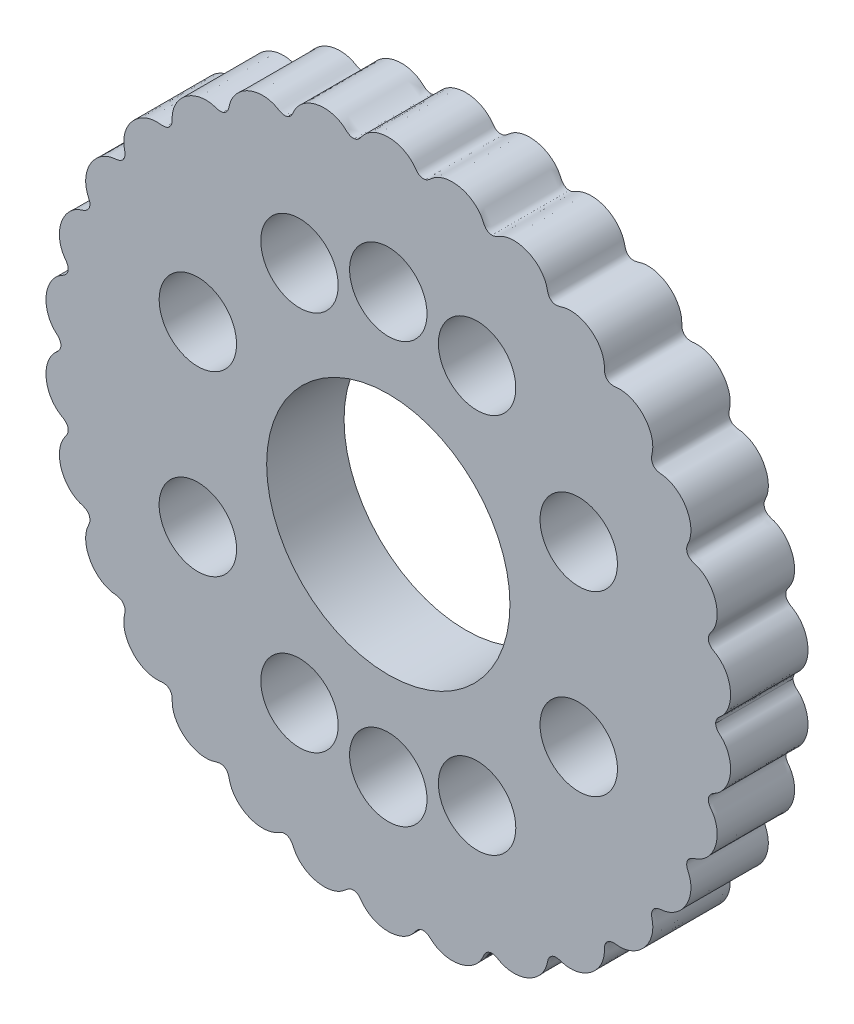
SolidWorks part; units mm, degrees
ref_plane "Plan de face" through (0, 0, 0) normal (0, 0, 1) x (1, 0, 0)
ref_plane "Plan de dessus" through (0, 0, 0) normal (0, 1, 0) x (1, 0, 0)
ref_plane "Plan de droite" through (0, 0, 0) normal (1, 0, 0) x (0, 0, -1)
sketch "Esquisse1" plane through (0, 0, 0) normal (0, 0, 1) x (1, 0, 0)
  line L0 (-1000, 0) -> (49000, 0) construction
  spline S0 degree 4 poles (29.8631, 8.2305) (29.8499, 8.1217) (29.8133, 7.9053) (29.7416, 7.64) (29.6157, 7.3353) (29.4839, 7.095) (29.3642, 6.911) (29.2467, 6.7537) (29.1538, 6.6056) (29.0902, 6.432) (29.0737, 6.2397) (29.1354, 6.023) (29.2904, 5.838) (29.4774, 5.7198) (29.6579, 5.6163) (29.8231, 5.5082) (30.0196, 5.3594) (30.2372, 5.1583) (30.5232, 4.8242) (30.8216, 4.3213) (31.0469, 3.679) (31.1337, 2.9091) (31.0567, 2.2277) (30.8902, 1.7108) (30.7109, 1.353) (30.5728, 1.1334) (30.4496, 0.9663) (30.3139, 0.8094) (30.1671, 0.6626) (30.0393, 0.549) (29.9425, 0.4546) (29.8803, 0.3777) (29.8449, 0.3262) (29.8141, 0.2716) (29.7888, 0.2141) (29.7717, 0.1632) (29.761, 0.1169) (29.7536, 0.0672) (29.7495, 0.017) (29.7494, -0.0206) (29.7556, -0.0898) (29.7678, -0.1499) (29.7904, -0.2203) (29.8284, -0.303) (29.8828, -0.3847) (29.9529, -0.4642) (30.04, -0.5488) (30.1416, -0.6407) (30.2572, -0.7512) (30.3813, -0.8854) (30.4962, -1.0277) (30.6276, -1.2147) (30.7721, -1.4641) (30.9126, -1.7829) (31.0276, -2.1744) (31.0935, -2.591) (31.107, -3.0187) (31.0662, -3.4508) (30.9693, -3.8803) (30.8145, -4.2991) (30.6117, -4.6792) (30.3965, -4.9766) (30.1917, -5.1998) (30.0146, -5.3603) (29.8643, -5.4786) (29.7061, -5.5858) (29.542, -5.684) (29.3671, -5.785) (29.2042, -5.9269) (29.0936, -6.1295) (29.0703, -6.371) (29.1391, -6.5914) (29.2598, -6.7697) (29.3791, -6.934) (29.4834, -7.0955) (29.5997, -7.3056) (29.715, -7.5703) (29.8147, -7.8969) (29.8798, -8.2857) (29.896, -8.684) (29.8631, -9.0858) (29.7829, -9.4799) (29.6574, -9.8612) (29.4885, -10.2243) (29.2783, -10.5643) (29.0303, -10.8742) (28.7824, -11.1148) (28.5506, -11.2952) (28.3468, -11.4258) (28.1768, -11.5188) (28.0006, -11.599) (27.8193, -11.6676) (27.6244, -11.7296) (27.4217, -11.8089) (27.242, -11.9571) (27.1301, -12.1734) (27.113, -12.404) (27.1707, -12.6114) (27.2542, -12.795) (27.3276, -12.9715) (27.3906, -13.1518) (27.4404, -13.3363) (27.4866, -13.5706) (27.5177, -13.8717) (27.5133, -14.2384) (27.4499, -14.6642) (27.3252, -15.0926) (27.1465, -15.4978) (26.919, -15.8739) (26.6474, -16.2153) (26.3365, -16.5168) (26.0024, -16.764) (25.654, -16.9563) (25.3418, -17.0779) (25.0791, -17.148) (24.8562, -17.1866) (24.6765, -17.2082) (24.4854, -17.2287) (24.2872, -17.2853) (24.1038, -17.4139) (23.9758, -17.6159) (23.9376, -17.8434) (23.9703, -18.0586) (24.0141, -18.2584) (24.0453, -18.4498) (24.0639, -18.6424) (24.0684, -18.8361) (24.0572, -19.0779) (24.0169, -19.3689) (23.9324, -19.7039) (23.7881, -20.0736) (23.5988, -20.4256) (23.3687, -20.7534) (23.1013, -21.0528) (22.8001, -21.3193) (22.4685, -21.5487) (22.1155, -21.7338) (21.7463, -21.8718) (21.4135, -21.9488) (21.1267, -21.9813) (20.8866, -21.9856) (20.6945, -21.9761) (20.4927, -21.9549) (20.2778, -21.9395) (20.0526, -21.9901) (19.8551, -22.131) (19.7349, -22.3281) (19.6935, -22.5401) (19.6935, -22.7421) (19.6905, -22.9333) (19.6768, -23.124) (19.6495, -23.3133) (19.599, -23.5469) (19.5081, -23.8358) (19.3582, -24.1709) (19.1304, -24.5365) (18.8451, -24.88) (18.5216, -25.1787) (18.1677, -25.4301) (17.7906, -25.6322) (17.3968, -25.7835) (17.0003, -25.8796) (16.6085, -25.9224) (16.2742, -25.9148) (16.002, -25.8785) (15.7793, -25.8278) (15.6036, -25.7769) (15.4169, -25.7147) (15.2087, -25.6689) (14.9779, -25.6954) (14.7639, -25.8189) (14.6256, -26.0056) (14.5611, -26.2088) (14.5217, -26.4015) (14.4779, -26.5791) (14.4104, -26.7974) (14.3058, -27.0513) (14.1452, -27.3445) (13.9122, -27.6625) (13.6308, -27.9579) (13.3029, -28.2232) (12.9393, -28.4488) (12.5446, -28.6295) (12.1242, -28.7604) (11.6841, -28.8357) (11.2535, -28.8501) (10.8884, -28.8124) (10.5927, -28.7466) (10.3651, -28.6736) (10.1875, -28.6026) (10.0156, -28.5191) (9.8485, -28.4261) (9.6736, -28.3252) (9.4693, -28.255) (9.2385, -28.2605) (9.0177, -28.3611) (8.8612, -28.5309) (8.7671, -28.7246) (8.6846, -28.91) (8.5968, -29.0812) (8.473, -29.2869) (8.3014, -29.519) (8.0684, -29.7687) (7.7643, -30.0195) (7.4274, -30.2327) (7.0631, -30.4051) (6.6816, -30.5327) (6.2887, -30.6146) (5.8897, -30.6499) (5.4902, -30.6379) (5.0979, -30.5781) (4.7655, -30.4837) (4.4934, -30.3731) (4.2784, -30.2619) (4.1128, -30.1612) (3.9553, -30.0487) (3.8052, -29.926) (3.6541, -29.7882) (3.484, -29.6523) (3.2679, -29.5716) (3.029, -29.5815) (2.8259, -29.676) (2.6778, -29.8193) (2.5645, -29.9746) (2.456, -30.1194) (2.311, -30.2931) (2.119, -30.4856) (1.8576, -30.6952) (1.5168, -30.9007) (1.1357, -31.0665) (0.7192, -31.185) (0.2877, -31.2495) (-0.1517, -31.2585) (-0.592, -31.2106) (-1.0254, -31.1045) (-1.4258, -30.9464) (-1.7456, -30.7669) (-1.9908, -30.5894) (-2.1706, -30.4322) (-2.3055, -30.2968) (-2.4301, -30.1521) (-2.5463, -30.0003) (-2.6635, -29.8363) (-2.8143, -29.6826) (-3.0226, -29.582) (-3.2659, -29.5708) (-3.484, -29.6523) (-3.654, -29.7882) (-3.8052, -29.926) (-3.9553, -30.0487) (-4.1128, -30.1612) (-4.2784, -30.2619) (-4.4934, -30.3731) (-4.7655, -30.4837) (-5.0979, -30.5781) (-5.4902, -30.6379) (-5.8897, -30.6499) (-6.2887, -30.6146) (-6.6816, -30.5327) (-7.0631, -30.4051) (-7.4274, -30.2327) (-7.7643, -30.0195) (-8.0684, -29.7687) (-8.3014, -29.519) (-8.473, -29.2869) (-8.5968, -29.0812) (-8.6846, -28.91) (-8.7671, -28.7246) (-8.8612, -28.5309) (-9.0177, -28.3611) (-9.2385, -28.2605) (-9.4693, -28.255) (-9.6736, -28.3252) (-9.8485, -28.4261) (-10.0156, -28.5191) (-10.1875, -28.6026) (-10.3651, -28.6736) (-10.5927, -28.7466) (-10.8884, -28.8124) (-11.2535, -28.8501) (-11.6841, -28.8357) (-12.1242, -28.7604) (-12.5446, -28.6295) (-12.9393, -28.4488) (-13.3029, -28.2232) (-13.6308, -27.9579) (-13.9122, -27.6625) (-14.1452, -27.3445) (-14.3058, -27.0513) (-14.4104, -26.7974) (-14.4779, -26.5791) (-14.5217, -26.4015) (-14.5611, -26.2088) (-14.6256, -26.0056) (-14.7639, -25.8189) (-14.9779, -25.6954) (-15.2087, -25.6689) (-15.4169, -25.7147) (-15.6036, -25.7769) (-15.7793, -25.8278) (-16.002, -25.8785) (-16.2742, -25.9148) (-16.6085, -25.9224) (-17.0003, -25.8796) (-17.3968, -25.7835) (-17.7906, -25.6322) (-18.1677, -25.4301) (-18.5216, -25.1787) (-18.8451, -24.88) (-19.1304, -24.5365) (-19.3582, -24.1709) (-19.5081, -23.8358) (-19.599, -23.5469) (-19.6495, -23.3133) (-19.6768, -23.124) (-19.6905, -22.9333) (-19.6935, -22.7421) (-19.6935, -22.5401) (-19.7349, -22.3281) (-19.8551, -22.131) (-20.0526, -21.9901) (-20.2778, -21.9395) (-20.4927, -21.9549) (-20.6945, -21.9761) (-20.8866, -21.9856) (-21.1267, -21.9813) (-21.4135, -21.9488) (-21.7463, -21.8718) (-22.1155, -21.7338) (-22.4685, -21.5487) (-22.8001, -21.3193) (-23.1013, -21.0528) (-23.3687, -20.7534) (-23.5988, -20.4256) (-23.7881, -20.0736) (-23.9324, -19.7039) (-24.0169, -19.3689) (-24.0572, -19.0779) (-24.0684, -18.8361) (-24.0639, -18.6424) (-24.0453, -18.4498) (-24.0141, -18.2584) (-23.9703, -18.0586) (-23.9376, -17.8434) (-23.9758, -17.6159) (-24.1038, -17.4139) (-24.2872, -17.2853) (-24.4854, -17.2287) (-24.6765, -17.2082) (-24.8562, -17.1866) (-25.0791, -17.148) (-25.3418, -17.0779) (-25.654, -16.9563) (-26.0024, -16.764) (-26.3365, -16.5168) (-26.6474, -16.2153) (-26.919, -15.8739) (-27.1465, -15.4978) (-27.3252, -15.0926) (-27.4499, -14.6642) (-27.5133, -14.2384) (-27.5177, -13.8717) (-27.4866, -13.5706) (-27.4404, -13.3363) (-27.3906, -13.1518) (-27.3276, -12.9715) (-27.2542, -12.795) (-27.1707, -12.6114) (-27.113, -12.404) (-27.1301, -12.1734) (-27.242, -11.9571) (-27.4217, -11.8089) (-27.6244, -11.7296) (-27.8193, -11.6676) (-28.0006, -11.599) (-28.1768, -11.5188) (-28.3468, -11.4258) (-28.5506, -11.2952) (-28.7824, -11.1148) (-29.0303, -10.8742) (-29.2783, -10.5643) (-29.4885, -10.2243) (-29.6574, -9.8612) (-29.7829, -9.4799) (-29.8631, -9.0858) (-29.896, -8.684) (-29.8798, -8.2857) (-29.8147, -7.8969) (-29.715, -7.5703) (-29.5997, -7.3056) (-29.4834, -7.0955) (-29.3791, -6.934) (-29.2598, -6.7697) (-29.1391, -6.5914) (-29.0703, -6.371) (-29.0936, -6.1295) (-29.2042, -5.9269) (-29.3671, -5.785) (-29.542, -5.684) (-29.7061, -5.5858) (-29.8643, -5.4786) (-30.0146, -5.3603) (-30.1917, -5.1998) (-30.3965, -4.9766) (-30.6117, -4.6792) (-30.8145, -4.2991) (-30.9693, -3.8803) (-31.0662, -3.4508) (-31.107, -3.0187) (-31.0935, -2.591) (-31.0276, -2.1744) (-30.9126, -1.7829) (-30.7537, -1.4222) (-30.58, -1.1364) (-30.4124, -0.919) (-30.2572, -0.7512) (-30.1416, -0.6407) (-30.04, -0.5488) (-29.9529, -0.4642) (-29.8828, -0.3847) (-29.8284, -0.303) (-29.7904, -0.2203) (-29.7678, -0.1499) (-29.7556, -0.0898) (-29.7494, -0.0206) (-29.7495, 0.0226) (-29.7561, 0.094) (-29.7693, 0.1557) (-29.7888, 0.2141) (-29.8141, 0.2716) (-29.8449, 0.3262) (-29.8803, 0.3778) (-29.9262, 0.4344) (-29.9834, 0.4947) (-30.0703, 0.5765) (-30.1854, 0.6811) (-30.3139, 0.8093) (-30.4835, 1.0056) (-30.6621, 1.2611) (-30.8291, 1.576) (-30.9678, 1.9517) (-31.0574, 2.3341) (-31.1011, 2.7166) (-31.1012, 3.1978) (-31.0148, 3.7704) (-30.8216, 4.3213) (-30.5232, 4.8242) (-30.2372, 5.1583) (-30.0196, 5.3594) (-29.8231, 5.5082) (-29.6579, 5.6163) (-29.4774, 5.7198) (-29.2904, 5.838) (-29.1354, 6.023) (-29.0737, 6.2397) (-29.0902, 6.432) (-29.1538, 6.6056) (-29.2467, 6.7537) (-29.3642, 6.911) (-29.4839, 7.095) (-29.6157, 7.3353) (-29.7416, 7.64) (-29.8133, 7.9053) (-29.8499, 8.1217) (-29.8631, 8.2305) knots 0 0 0 0 0 0.003392 0.006784 0.00848 0.010176 0.011872 0.013568 0.014566 0.015563 0.017559 0.01944 0.02132 0.022846 0.024371 0.025896 0.027421 0.030471 0.033522 0.039468 0.045414 0.051361 0.057307 0.060517 0.062121 0.063726 0.065331 0.066935 0.06854 0.070145 0.070628 0.071112 0.071596 0.07208 0.072564 0.073048 0.073289 0.073531 0.074015 0.07448 0.074945 0.07541 0.075875 0.076805 0.077735 0.078442 0.079149 0.080563 0.081977 0.083391 0.084805 0.086218 0.089046 0.092302 0.095557 0.098813 0.102069 0.105514 0.10896 0.112405 0.115851 0.118808 0.120287 0.121766 0.123244 0.124723 0.126202 0.12768 0.1295 0.131319 0.133154 0.134989 0.136475 0.137961 0.139448 0.140934 0.143906 0.146878 0.14999 0.153103 0.156215 0.159327 0.162414 0.1655 0.168586 0.171672 0.174668 0.176165 0.177663 0.179161 0.180659 0.182156 0.183654 0.185506 0.187357 0.189175 0.190994 0.192471 0.193949 0.195426 0.196904 0.198382 0.199859 0.202814 0.206257 0.2097 0.213143 0.216586 0.219928 0.22327 0.226613 0.229955 0.232755 0.235555 0.236955 0.238355 0.239755 0.241155 0.242909 0.244663 0.246515 0.248366 0.249864 0.251362 0.252859 0.254357 0.255855 0.257353 0.260348 0.263434 0.266521 0.269607 0.272693 0.275805 0.278918 0.28203 0.285143 0.288115 0.291087 0.292573 0.294059 0.295545 0.297031 0.298866 0.300701 0.302521 0.30434 0.305819 0.307297 0.308776 0.310255 0.311733 0.313212 0.31617 0.319615 0.323061 0.326506 0.329952 0.333207 0.336463 0.339719 0.342974 0.345802 0.34863 0.350043 0.351457 0.352871 0.354285 0.356145 0.358005 0.359865 0.361725 0.363139 0.364553 0.365967 0.367381 0.370208 0.373036 0.376292 0.379547 0.382803 0.386059 0.389504 0.39295 0.396395 0.399841 0.402798 0.404277 0.405755 0.407234 0.408713 0.410191 0.41167 0.41349 0.415309 0.417144 0.418979 0.420465 0.421951 0.423437 0.424923 0.427896 0.430868 0.43398 0.437092 0.440205 0.443317 0.446403 0.44949 0.452576 0.455662 0.458657 0.460155 0.461653 0.463151 0.464649 0.466146 0.467644 0.469495 0.471347 0.473101 0.474856 0.476256 0.477656 0.479056 0.480456 0.483256 0.486055 0.489398 0.49274 0.496082 0.499424 0.502867 0.50631 0.509753 0.513196 0.516151 0.517629 0.519106 0.520584 0.522061 0.523539 0.525016 0.526835 0.528653 0.530505 0.532356 0.533854 0.535351 0.536849 0.538347 0.539845 0.541343 0.544338 0.547424 0.55051 0.553597 0.556683 0.559795 0.562908 0.56602 0.569132 0.572104 0.575077 0.576563 0.578049 0.579535 0.581021 0.582856 0.584691 0.58651 0.58833 0.589809 0.591287 0.592766 0.594245 0.595723 0.597202 0.600159 0.603605 0.60705 0.610496 0.613941 0.617197 0.620453 0.623708 0.626964 0.629792 0.632619 0.634033 0.635447 0.636861 0.638275 0.640135 0.641995 0.643855 0.645715 0.647129 0.648543 0.649957 0.65137 0.654198 0.657026 0.660281 0.663537 0.666793 0.670048 0.673494 0.676939 0.680385 0.68383 0.686788 0.688267 0.689745 0.691224 0.692703 0.694181 0.69566 0.697479 0.699299 0.701134 0.702969 0.704455 0.705941 0.707427 0.708913 0.711885 0.714857 0.71797 0.721082 0.724195 0.727307 0.730393 0.733479 0.736566 0.739652 0.742647 0.744145 0.745643 0.747141 0.748638 0.750136 0.751634 0.753485 0.755337 0.757091 0.758845 0.760245 0.761645 0.763045 0.764445 0.767245 0.770045 0.773387 0.77673 0.780072 0.783414 0.786857 0.7903 0.793743 0.797186 0.800141 0.801618 0.803096 0.804574 0.806051 0.807529 0.809006 0.810825 0.812643 0.814494 0.816346 0.817844 0.819341 0.820839 0.822337 0.823835 0.825332 0.828328 0.831414 0.8345 0.837586 0.840673 0.843785 0.846897 0.85001 0.853122 0.856094 0.859066 0.860552 0.862039 0.863525 0.865011 0.866846 0.868681 0.8705 0.87232 0.873798 0.875277 0.876756 0.878234 0.879713 0.881192 0.884149 0.887595 0.89104 0.894486 0.897931 0.901187 0.904443 0.907698 0.910954 0.913782 0.916609 0.918023 0.919437 0.920851 0.921558 0.922265 0.923195 0.924125 0.92459 0.925055 0.92552 0.925985 0.926469 0.926952 0.927436 0.92792 0.928404 0.928888 0.929372 0.929855 0.930658 0.93146 0.933065 0.934669 0.936274 0.939483 0.942693 0.945666 0.948639 0.951612 0.954586 0.960532 0.966478 0.969529 0.972579 0.974104 0.975629 0.977154 0.97868 0.98056 0.982441 0.984437 0.985434 0.986432 0.988128 0.989824 0.99152 0.993216 0.996608 1 1 1 1 1 construction
  spline S1 degree 4 poles (29.75, 0) (29.75, -0.0128) (29.751, -0.0384) (29.7556, -0.0898) (29.7678, -0.1499) (29.7904, -0.2203) (29.8284, -0.303) (29.8828, -0.3847) (29.9529, -0.4642) (30.04, -0.5488) (30.1416, -0.6407) (30.2572, -0.7512) (30.3813, -0.8854) (30.4962, -1.0277) (30.6276, -1.2147) (30.7721, -1.4641) (30.9126, -1.7829) (31.0276, -2.1744) (31.0935, -2.591) (31.107, -3.0187) (31.0662, -3.4508) (30.9693, -3.8803) (30.8145, -4.2991) (30.6117, -4.6792) (30.3965, -4.9766) (30.1917, -5.1998) (30.0146, -5.3603) (29.8643, -5.4786) (29.7061, -5.5858) (29.542, -5.684) (29.3671, -5.785) (29.2042, -5.9269) (29.0936, -6.1295) (29.0703, -6.371) (29.1391, -6.5914) (29.2598, -6.7697) (29.3791, -6.934) (29.4834, -7.0955) (29.5997, -7.3056) (29.715, -7.5703) (29.8147, -7.8969) (29.8798, -8.2857) (29.896, -8.684) (29.8631, -9.0858) (29.7829, -9.4799) (29.6574, -9.8612) (29.4885, -10.2243) (29.2783, -10.5643) (29.0303, -10.8742) (28.7824, -11.1148) (28.5506, -11.2952) (28.3468, -11.4258) (28.1768, -11.5188) (28.0006, -11.599) (27.8193, -11.6676) (27.6244, -11.7296) (27.4217, -11.8089) (27.242, -11.9571) (27.1301, -12.1734) (27.113, -12.404) (27.1707, -12.6114) (27.2542, -12.795) (27.3276, -12.9715) (27.3906, -13.1518) (27.4404, -13.3363) (27.4866, -13.5706) (27.5177, -13.8717) (27.5133, -14.2384) (27.4499, -14.6642) (27.3252, -15.0926) (27.1465, -15.4978) (26.919, -15.8739) (26.6474, -16.2153) (26.3365, -16.5168) (26.0024, -16.764) (25.654, -16.9563) (25.3418, -17.0779) (25.0791, -17.148) (24.8562, -17.1866) (24.6765, -17.2082) (24.4854, -17.2287) (24.2872, -17.2853) (24.1038, -17.4139) (23.9758, -17.6159) (23.9376, -17.8434) (23.9703, -18.0586) (24.0141, -18.2584) (24.0453, -18.4498) (24.0639, -18.6424) (24.0684, -18.8361) (24.0572, -19.0779) (24.0169, -19.3689) (23.9324, -19.7039) (23.7881, -20.0736) (23.5988, -20.4256) (23.3687, -20.7534) (23.1013, -21.0528) (22.8001, -21.3193) (22.4685, -21.5487) (22.1155, -21.7338) (21.7463, -21.8718) (21.4135, -21.9488) (21.1267, -21.9813) (20.8866, -21.9856) (20.6945, -21.9761) (20.4927, -21.9549) (20.2778, -21.9395) (20.0526, -21.9901) (19.8551, -22.131) (19.7349, -22.3281) (19.6935, -22.5401) (19.6935, -22.7421) (19.6905, -22.9333) (19.6768, -23.124) (19.6495, -23.3133) (19.599, -23.5469) (19.5081, -23.8358) (19.3582, -24.1709) (19.1304, -24.5365) (18.8451, -24.88) (18.5216, -25.1787) (18.1677, -25.4301) (17.7906, -25.6322) (17.3968, -25.7835) (17.0003, -25.8796) (16.6085, -25.9224) (16.2742, -25.9148) (16.002, -25.8785) (15.7793, -25.8278) (15.6036, -25.7769) (15.4169, -25.7147) (15.2087, -25.6689) (14.9779, -25.6954) (14.7639, -25.8189) (14.6256, -26.0056) (14.5611, -26.2088) (14.5217, -26.4015) (14.4779, -26.5791) (14.4104, -26.7974) (14.3058, -27.0513) (14.1452, -27.3445) (13.9122, -27.6625) (13.6308, -27.9579) (13.3029, -28.2232) (12.9393, -28.4488) (12.5446, -28.6295) (12.1242, -28.7604) (11.6841, -28.8357) (11.2535, -28.8501) (10.8884, -28.8124) (10.5927, -28.7466) (10.3651, -28.6736) (10.1875, -28.6026) (10.0156, -28.5191) (9.8485, -28.4261) (9.6736, -28.3252) (9.4693, -28.255) (9.2385, -28.2605) (9.0177, -28.3611) (8.8612, -28.5309) (8.7671, -28.7246) (8.6846, -28.91) (8.5968, -29.0812) (8.473, -29.2869) (8.3014, -29.519) (8.0684, -29.7687) (7.7643, -30.0195) (7.4274, -30.2327) (7.0631, -30.4051) (6.6816, -30.5327) (6.2887, -30.6146) (5.8897, -30.6499) (5.4902, -30.6379) (5.0979, -30.5781) (4.7655, -30.4837) (4.4934, -30.3731) (4.2784, -30.2619) (4.1128, -30.1612) (3.9553, -30.0487) (3.8052, -29.926) (3.6541, -29.7882) (3.484, -29.6523) (3.2679, -29.5716) (3.029, -29.5815) (2.8259, -29.676) (2.6778, -29.8193) (2.5645, -29.9746) (2.456, -30.1194) (2.311, -30.2931) (2.119, -30.4856) (1.8576, -30.6952) (1.5168, -30.9007) (1.1357, -31.0665) (0.7192, -31.185) (0.2877, -31.2495) (-0.1517, -31.2585) (-0.592, -31.2106) (-1.0254, -31.1045) (-1.4258, -30.9464) (-1.7456, -30.7669) (-1.9908, -30.5894) (-2.1706, -30.4322) (-2.3055, -30.2968) (-2.4301, -30.1521) (-2.5463, -30.0003) (-2.6635, -29.8363) (-2.8143, -29.6826) (-3.0226, -29.582) (-3.2659, -29.5708) (-3.484, -29.6523) (-3.654, -29.7882) (-3.8052, -29.926) (-3.9553, -30.0487) (-4.1128, -30.1612) (-4.2784, -30.2619) (-4.4934, -30.3731) (-4.7655, -30.4837) (-5.0979, -30.5781) (-5.4902, -30.6379) (-5.8897, -30.6499) (-6.2887, -30.6146) (-6.6816, -30.5327) (-7.0631, -30.4051) (-7.4274, -30.2327) (-7.7643, -30.0195) (-8.0684, -29.7687) (-8.3014, -29.519) (-8.473, -29.2869) (-8.5968, -29.0812) (-8.6846, -28.91) (-8.7671, -28.7246) (-8.8612, -28.5309) (-9.0177, -28.3611) (-9.2385, -28.2605) (-9.4693, -28.255) (-9.6736, -28.3252) (-9.8485, -28.4261) (-10.0156, -28.5191) (-10.1875, -28.6026) (-10.3651, -28.6736) (-10.5927, -28.7466) (-10.8884, -28.8124) (-11.2535, -28.8501) (-11.6841, -28.8357) (-12.1242, -28.7604) (-12.5446, -28.6295) (-12.9393, -28.4488) (-13.3029, -28.2232) (-13.6308, -27.9579) (-13.9122, -27.6625) (-14.1452, -27.3445) (-14.3058, -27.0513) (-14.4104, -26.7974) (-14.4779, -26.5791) (-14.5217, -26.4015) (-14.5611, -26.2088) (-14.6256, -26.0056) (-14.7639, -25.8189) (-14.9779, -25.6954) (-15.2087, -25.6689) (-15.4169, -25.7147) (-15.6036, -25.7769) (-15.7793, -25.8278) (-16.002, -25.8785) (-16.2742, -25.9148) (-16.6085, -25.9224) (-17.0003, -25.8796) (-17.3968, -25.7835) (-17.7906, -25.6322) (-18.1677, -25.4301) (-18.5216, -25.1787) (-18.8451, -24.88) (-19.1304, -24.5365) (-19.3582, -24.1709) (-19.5081, -23.8358) (-19.599, -23.5469) (-19.6495, -23.3133) (-19.6768, -23.124) (-19.6905, -22.9333) (-19.6935, -22.7421) (-19.6935, -22.5401) (-19.7349, -22.3281) (-19.8551, -22.131) (-20.0526, -21.9901) (-20.2778, -21.9395) (-20.4927, -21.9549) (-20.6945, -21.9761) (-20.8866, -21.9856) (-21.1267, -21.9813) (-21.4135, -21.9488) (-21.7463, -21.8718) (-22.1155, -21.7338) (-22.4685, -21.5487) (-22.8001, -21.3193) (-23.1013, -21.0528) (-23.3687, -20.7534) (-23.5988, -20.4256) (-23.7881, -20.0736) (-23.9324, -19.7039) (-24.0169, -19.3689) (-24.0572, -19.0779) (-24.0684, -18.8361) (-24.0639, -18.6424) (-24.0453, -18.4498) (-24.0141, -18.2584) (-23.9703, -18.0586) (-23.9376, -17.8434) (-23.9758, -17.6159) (-24.1038, -17.4139) (-24.2872, -17.2853) (-24.4854, -17.2287) (-24.6765, -17.2082) (-24.8562, -17.1866) (-25.0791, -17.148) (-25.3418, -17.0779) (-25.654, -16.9563) (-26.0024, -16.764) (-26.3365, -16.5168) (-26.6474, -16.2153) (-26.919, -15.8739) (-27.1465, -15.4978) (-27.3252, -15.0926) (-27.4499, -14.6642) (-27.5133, -14.2384) (-27.5177, -13.8717) (-27.4866, -13.5706) (-27.4404, -13.3363) (-27.3906, -13.1518) (-27.3276, -12.9715) (-27.2542, -12.795) (-27.1707, -12.6114) (-27.113, -12.404) (-27.1301, -12.1734) (-27.242, -11.9571) (-27.4217, -11.8089) (-27.6244, -11.7296) (-27.8193, -11.6676) (-28.0006, -11.599) (-28.1768, -11.5188) (-28.3468, -11.4258) (-28.5506, -11.2952) (-28.7824, -11.1148) (-29.0303, -10.8742) (-29.2783, -10.5643) (-29.4885, -10.2243) (-29.6574, -9.8612) (-29.7829, -9.4799) (-29.8631, -9.0858) (-29.896, -8.684) (-29.8798, -8.2857) (-29.8147, -7.8969) (-29.715, -7.5703) (-29.5997, -7.3056) (-29.4834, -7.0955) (-29.3791, -6.934) (-29.2598, -6.7697) (-29.1391, -6.5914) (-29.0703, -6.371) (-29.0936, -6.1295) (-29.2042, -5.9269) (-29.3671, -5.785) (-29.542, -5.684) (-29.7061, -5.5858) (-29.8643, -5.4786) (-30.0146, -5.3603) (-30.1917, -5.1998) (-30.3965, -4.9766) (-30.6117, -4.6792) (-30.8145, -4.2991) (-30.9693, -3.8803) (-31.0662, -3.4508) (-31.107, -3.0187) (-31.0935, -2.591) (-31.0276, -2.1744) (-30.9126, -1.7829) (-30.7537, -1.4222) (-30.58, -1.1364) (-30.4124, -0.919) (-30.2572, -0.7512) (-30.1416, -0.6407) (-30.04, -0.5488) (-29.9529, -0.4642) (-29.8828, -0.3847) (-29.8284, -0.303) (-29.7904, -0.2203) (-29.7678, -0.1499) (-29.7556, -0.0898) (-29.751, -0.0384) (-29.75, -0.0128) (-29.75, 0) knots 0.074015 0.074015 0.074015 0.074015 0.074015 0.07448 0.074945 0.07541 0.075875 0.076805 0.077735 0.078442 0.079149 0.080563 0.081977 0.083391 0.084805 0.086218 0.089046 0.092302 0.095557 0.098813 0.102069 0.105514 0.10896 0.112405 0.115851 0.118808 0.120287 0.121766 0.123244 0.124723 0.126202 0.12768 0.1295 0.131319 0.133154 0.134989 0.136475 0.137961 0.139448 0.140934 0.143906 0.146878 0.14999 0.153103 0.156215 0.159327 0.162414 0.1655 0.168586 0.171672 0.174668 0.176165 0.177663 0.179161 0.180659 0.182156 0.183654 0.185506 0.187357 0.189175 0.190994 0.192471 0.193949 0.195426 0.196904 0.198382 0.199859 0.202814 0.206257 0.2097 0.213143 0.216586 0.219928 0.22327 0.226613 0.229955 0.232755 0.235555 0.236955 0.238355 0.239755 0.241155 0.242909 0.244663 0.246515 0.248366 0.249864 0.251362 0.252859 0.254357 0.255855 0.257353 0.260348 0.263434 0.266521 0.269607 0.272693 0.275805 0.278918 0.28203 0.285143 0.288115 0.291087 0.292573 0.294059 0.295545 0.297031 0.298866 0.300701 0.302521 0.30434 0.305819 0.307297 0.308776 0.310255 0.311733 0.313212 0.31617 0.319615 0.323061 0.326506 0.329952 0.333207 0.336463 0.339719 0.342974 0.345802 0.34863 0.350043 0.351457 0.352871 0.354285 0.356145 0.358005 0.359865 0.361725 0.363139 0.364553 0.365967 0.367381 0.370208 0.373036 0.376292 0.379547 0.382803 0.386059 0.389504 0.39295 0.396395 0.399841 0.402798 0.404277 0.405755 0.407234 0.408713 0.410191 0.41167 0.41349 0.415309 0.417144 0.418979 0.420465 0.421951 0.423437 0.424923 0.427896 0.430868 0.43398 0.437092 0.440205 0.443317 0.446403 0.44949 0.452576 0.455662 0.458657 0.460155 0.461653 0.463151 0.464649 0.466146 0.467644 0.469495 0.471347 0.473101 0.474856 0.476256 0.477656 0.479056 0.480456 0.483256 0.486055 0.489398 0.49274 0.496082 0.499424 0.502867 0.50631 0.509753 0.513196 0.516151 0.517629 0.519106 0.520584 0.522061 0.523539 0.525016 0.526835 0.528653 0.530505 0.532356 0.533854 0.535351 0.536849 0.538347 0.539845 0.541343 0.544338 0.547424 0.55051 0.553597 0.556683 0.559795 0.562908 0.56602 0.569132 0.572104 0.575077 0.576563 0.578049 0.579535 0.581021 0.582856 0.584691 0.58651 0.58833 0.589809 0.591287 0.592766 0.594245 0.595723 0.597202 0.600159 0.603605 0.60705 0.610496 0.613941 0.617197 0.620453 0.623708 0.626964 0.629792 0.632619 0.634033 0.635447 0.636861 0.638275 0.640135 0.641995 0.643855 0.645715 0.647129 0.648543 0.649957 0.65137 0.654198 0.657026 0.660281 0.663537 0.666793 0.670048 0.673494 0.676939 0.680385 0.68383 0.686788 0.688267 0.689745 0.691224 0.692703 0.694181 0.69566 0.697479 0.699299 0.701134 0.702969 0.704455 0.705941 0.707427 0.708913 0.711885 0.714857 0.71797 0.721082 0.724195 0.727307 0.730393 0.733479 0.736566 0.739652 0.742647 0.744145 0.745643 0.747141 0.748638 0.750136 0.751634 0.753485 0.755337 0.757091 0.758845 0.760245 0.761645 0.763045 0.764445 0.767245 0.770045 0.773387 0.77673 0.780072 0.783414 0.786857 0.7903 0.793743 0.797186 0.800141 0.801618 0.803096 0.804574 0.806051 0.807529 0.809006 0.810825 0.812643 0.814494 0.816346 0.817844 0.819341 0.820839 0.822337 0.823835 0.825332 0.828328 0.831414 0.8345 0.837586 0.840673 0.843785 0.846897 0.85001 0.853122 0.856094 0.859066 0.860552 0.862039 0.863525 0.865011 0.866846 0.868681 0.8705 0.87232 0.873798 0.875277 0.876756 0.878234 0.879713 0.881192 0.884149 0.887595 0.89104 0.894486 0.897931 0.901187 0.904443 0.907698 0.910954 0.913782 0.916609 0.918023 0.919437 0.920851 0.921558 0.922265 0.923195 0.924125 0.92459 0.925055 0.92552 0.925985 0.925985 0.925985 0.925985 0.925985 construction
  spline S2 degree 4 poles (29.75, 0) (29.75, 0.0128) (29.751, 0.0384) (29.7556, 0.0898) (29.7678, 0.1499) (29.7904, 0.2203) (29.8284, 0.303) (29.8828, 0.3847) (29.9529, 0.4642) (30.04, 0.5488) (30.1416, 0.6407) (30.2572, 0.7512) (30.3813, 0.8854) (30.4962, 1.0277) (30.6276, 1.2147) (30.7721, 1.4641) (30.9126, 1.7829) (31.0276, 2.1744) (31.0935, 2.591) (31.107, 3.0187) (31.0662, 3.4508) (30.9693, 3.8803) (30.8145, 4.2991) (30.6117, 4.6792) (30.3965, 4.9766) (30.1917, 5.1998) (30.0146, 5.3603) (29.8643, 5.4786) (29.7061, 5.5858) (29.542, 5.684) (29.3671, 5.785) (29.2042, 5.9269) (29.0936, 6.1295) (29.0703, 6.371) (29.1391, 6.5914) (29.2598, 6.7697) (29.3791, 6.934) (29.4834, 7.0955) (29.5997, 7.3056) (29.715, 7.5703) (29.8147, 7.8969) (29.8798, 8.2857) (29.896, 8.684) (29.8631, 9.0858) (29.7829, 9.4799) (29.6574, 9.8612) (29.4885, 10.2243) (29.2783, 10.5643) (29.0303, 10.8742) (28.7824, 11.1148) (28.5506, 11.2952) (28.3468, 11.4258) (28.1768, 11.5188) (28.0006, 11.599) (27.8193, 11.6676) (27.6244, 11.7296) (27.4217, 11.8089) (27.242, 11.9571) (27.1301, 12.1734) (27.113, 12.404) (27.1707, 12.6114) (27.2542, 12.795) (27.3276, 12.9715) (27.3906, 13.1518) (27.4404, 13.3363) (27.4866, 13.5706) (27.5177, 13.8717) (27.5133, 14.2384) (27.4499, 14.6642) (27.3252, 15.0926) (27.1465, 15.4978) (26.919, 15.8739) (26.6474, 16.2153) (26.3365, 16.5168) (26.0024, 16.764) (25.654, 16.9563) (25.3418, 17.0779) (25.0791, 17.148) (24.8562, 17.1866) (24.6765, 17.2082) (24.4854, 17.2287) (24.2872, 17.2853) (24.1038, 17.4139) (23.9758, 17.6159) (23.9376, 17.8434) (23.9703, 18.0586) (24.0141, 18.2584) (24.0453, 18.4498) (24.0639, 18.6424) (24.0684, 18.8361) (24.0572, 19.0779) (24.0169, 19.3689) (23.9324, 19.7039) (23.7881, 20.0736) (23.5988, 20.4256) (23.3687, 20.7534) (23.1013, 21.0528) (22.8001, 21.3193) (22.4685, 21.5487) (22.1155, 21.7338) (21.7463, 21.8718) (21.4135, 21.9488) (21.1267, 21.9813) (20.8866, 21.9856) (20.6945, 21.9761) (20.4927, 21.9549) (20.2778, 21.9395) (20.0526, 21.9901) (19.8551, 22.131) (19.7349, 22.3281) (19.6935, 22.5401) (19.6935, 22.7421) (19.6905, 22.9333) (19.6768, 23.124) (19.6495, 23.3133) (19.599, 23.5469) (19.5081, 23.8358) (19.3582, 24.1709) (19.1304, 24.5365) (18.8451, 24.88) (18.5216, 25.1787) (18.1677, 25.4301) (17.7906, 25.6322) (17.3968, 25.7835) (17.0003, 25.8796) (16.6085, 25.9224) (16.2742, 25.9148) (16.002, 25.8785) (15.7793, 25.8278) (15.6036, 25.7769) (15.4169, 25.7147) (15.2087, 25.6689) (14.9779, 25.6954) (14.7639, 25.8189) (14.6256, 26.0056) (14.5611, 26.2088) (14.5217, 26.4015) (14.4779, 26.5791) (14.4104, 26.7974) (14.3058, 27.0513) (14.1452, 27.3445) (13.9122, 27.6625) (13.6308, 27.9579) (13.3029, 28.2232) (12.9393, 28.4488) (12.5446, 28.6295) (12.1242, 28.7604) (11.6841, 28.8357) (11.2535, 28.8501) (10.8884, 28.8124) (10.5927, 28.7466) (10.3651, 28.6736) (10.1875, 28.6026) (10.0156, 28.5191) (9.8485, 28.4261) (9.6736, 28.3252) (9.4693, 28.255) (9.2385, 28.2605) (9.0177, 28.3611) (8.8612, 28.5309) (8.7671, 28.7246) (8.6846, 28.91) (8.5968, 29.0812) (8.473, 29.2869) (8.3014, 29.519) (8.0684, 29.7687) (7.7643, 30.0195) (7.4274, 30.2327) (7.0631, 30.4051) (6.6816, 30.5327) (6.2887, 30.6146) (5.8897, 30.6499) (5.4902, 30.6379) (5.0979, 30.5781) (4.7655, 30.4837) (4.4934, 30.3731) (4.2784, 30.2619) (4.1128, 30.1612) (3.9553, 30.0487) (3.8052, 29.926) (3.6541, 29.7882) (3.484, 29.6523) (3.2679, 29.5716) (3.029, 29.5815) (2.8259, 29.676) (2.6778, 29.8193) (2.5645, 29.9746) (2.456, 30.1194) (2.311, 30.2931) (2.119, 30.4856) (1.8576, 30.6952) (1.5168, 30.9007) (1.1357, 31.0665) (0.7192, 31.185) (0.2877, 31.2495) (-0.1517, 31.2585) (-0.592, 31.2106) (-1.0254, 31.1045) (-1.4258, 30.9464) (-1.7456, 30.7669) (-1.9908, 30.5894) (-2.1706, 30.4322) (-2.3055, 30.2968) (-2.4301, 30.1521) (-2.5463, 30.0003) (-2.6635, 29.8363) (-2.8143, 29.6826) (-3.0226, 29.582) (-3.2659, 29.5708) (-3.484, 29.6523) (-3.654, 29.7882) (-3.8052, 29.926) (-3.9553, 30.0487) (-4.1128, 30.1612) (-4.2784, 30.2619) (-4.4934, 30.3731) (-4.7655, 30.4837) (-5.0979, 30.5781) (-5.4902, 30.6379) (-5.8897, 30.6499) (-6.2887, 30.6146) (-6.6816, 30.5327) (-7.0631, 30.4051) (-7.4274, 30.2327) (-7.7643, 30.0195) (-8.0684, 29.7687) (-8.3014, 29.519) (-8.473, 29.2869) (-8.5968, 29.0812) (-8.6846, 28.91) (-8.7671, 28.7246) (-8.8612, 28.5309) (-9.0177, 28.3611) (-9.2385, 28.2605) (-9.4693, 28.255) (-9.6736, 28.3252) (-9.8485, 28.4261) (-10.0156, 28.5191) (-10.1875, 28.6026) (-10.3651, 28.6736) (-10.5927, 28.7466) (-10.8884, 28.8124) (-11.2535, 28.8501) (-11.6841, 28.8357) (-12.1242, 28.7604) (-12.5446, 28.6295) (-12.9393, 28.4488) (-13.3029, 28.2232) (-13.6308, 27.9579) (-13.9122, 27.6625) (-14.1452, 27.3445) (-14.3058, 27.0513) (-14.4104, 26.7974) (-14.4779, 26.5791) (-14.5217, 26.4015) (-14.5611, 26.2088) (-14.6256, 26.0056) (-14.7639, 25.8189) (-14.9779, 25.6954) (-15.2087, 25.6689) (-15.4169, 25.7147) (-15.6036, 25.7769) (-15.7793, 25.8278) (-16.002, 25.8785) (-16.2742, 25.9148) (-16.6085, 25.9224) (-17.0003, 25.8796) (-17.3968, 25.7835) (-17.7906, 25.6322) (-18.1677, 25.4301) (-18.5216, 25.1787) (-18.8451, 24.88) (-19.1304, 24.5365) (-19.3582, 24.1709) (-19.5081, 23.8358) (-19.599, 23.5469) (-19.6495, 23.3133) (-19.6768, 23.124) (-19.6905, 22.9333) (-19.6935, 22.7421) (-19.6935, 22.5401) (-19.7349, 22.3281) (-19.8551, 22.131) (-20.0526, 21.9901) (-20.2778, 21.9395) (-20.4927, 21.9549) (-20.6945, 21.9761) (-20.8866, 21.9856) (-21.1267, 21.9813) (-21.4135, 21.9488) (-21.7463, 21.8718) (-22.1155, 21.7338) (-22.4685, 21.5487) (-22.8001, 21.3193) (-23.1013, 21.0528) (-23.3687, 20.7534) (-23.5988, 20.4256) (-23.7881, 20.0736) (-23.9324, 19.7039) (-24.0169, 19.3689) (-24.0572, 19.0779) (-24.0684, 18.8361) (-24.0639, 18.6424) (-24.0453, 18.4498) (-24.0141, 18.2584) (-23.9703, 18.0586) (-23.9376, 17.8434) (-23.9758, 17.6159) (-24.1038, 17.4139) (-24.2872, 17.2853) (-24.4854, 17.2287) (-24.6765, 17.2082) (-24.8562, 17.1866) (-25.0791, 17.148) (-25.3418, 17.0779) (-25.654, 16.9563) (-26.0024, 16.764) (-26.3365, 16.5168) (-26.6474, 16.2153) (-26.919, 15.8739) (-27.1465, 15.4978) (-27.3252, 15.0926) (-27.4499, 14.6642) (-27.5133, 14.2384) (-27.5177, 13.8717) (-27.4866, 13.5706) (-27.4404, 13.3363) (-27.3906, 13.1518) (-27.3276, 12.9715) (-27.2542, 12.795) (-27.1707, 12.6114) (-27.113, 12.404) (-27.1301, 12.1734) (-27.242, 11.9571) (-27.4217, 11.8089) (-27.6244, 11.7296) (-27.8193, 11.6676) (-28.0006, 11.599) (-28.1768, 11.5188) (-28.3468, 11.4258) (-28.5506, 11.2952) (-28.7824, 11.1148) (-29.0303, 10.8742) (-29.2783, 10.5643) (-29.4885, 10.2243) (-29.6574, 9.8612) (-29.7829, 9.4799) (-29.8631, 9.0858) (-29.896, 8.684) (-29.8798, 8.2857) (-29.8147, 7.8969) (-29.715, 7.5703) (-29.5997, 7.3056) (-29.4834, 7.0955) (-29.3791, 6.934) (-29.2598, 6.7697) (-29.1391, 6.5914) (-29.0703, 6.371) (-29.0936, 6.1295) (-29.2042, 5.9269) (-29.3671, 5.785) (-29.542, 5.684) (-29.7061, 5.5858) (-29.8643, 5.4786) (-30.0146, 5.3603) (-30.1917, 5.1998) (-30.3965, 4.9766) (-30.6117, 4.6792) (-30.8145, 4.2991) (-30.9693, 3.8803) (-31.0662, 3.4508) (-31.107, 3.0187) (-31.0935, 2.591) (-31.0276, 2.1744) (-30.9126, 1.7829) (-30.7537, 1.4222) (-30.58, 1.1364) (-30.4124, 0.919) (-30.2572, 0.7512) (-30.1416, 0.6407) (-30.04, 0.5488) (-29.9529, 0.4642) (-29.8828, 0.3847) (-29.8284, 0.303) (-29.7904, 0.2203) (-29.7678, 0.1499) (-29.7556, 0.0898) (-29.751, 0.0384) (-29.75, 0.0128) (-29.75, 0) knots 0.074015 0.074015 0.074015 0.074015 0.074015 0.07448 0.074945 0.07541 0.075875 0.076805 0.077735 0.078442 0.079149 0.080563 0.081977 0.083391 0.084805 0.086218 0.089046 0.092302 0.095557 0.098813 0.102069 0.105514 0.10896 0.112405 0.115851 0.118808 0.120287 0.121766 0.123244 0.124723 0.126202 0.12768 0.1295 0.131319 0.133154 0.134989 0.136475 0.137961 0.139448 0.140934 0.143906 0.146878 0.14999 0.153103 0.156215 0.159327 0.162414 0.1655 0.168586 0.171672 0.174668 0.176165 0.177663 0.179161 0.180659 0.182156 0.183654 0.185506 0.187357 0.189175 0.190994 0.192471 0.193949 0.195426 0.196904 0.198382 0.199859 0.202814 0.206257 0.2097 0.213143 0.216586 0.219928 0.22327 0.226613 0.229955 0.232755 0.235555 0.236955 0.238355 0.239755 0.241155 0.242909 0.244663 0.246515 0.248366 0.249864 0.251362 0.252859 0.254357 0.255855 0.257353 0.260348 0.263434 0.266521 0.269607 0.272693 0.275805 0.278918 0.28203 0.285143 0.288115 0.291087 0.292573 0.294059 0.295545 0.297031 0.298866 0.300701 0.302521 0.30434 0.305819 0.307297 0.308776 0.310255 0.311733 0.313212 0.31617 0.319615 0.323061 0.326506 0.329952 0.333207 0.336463 0.339719 0.342974 0.345802 0.34863 0.350043 0.351457 0.352871 0.354285 0.356145 0.358005 0.359865 0.361725 0.363139 0.364553 0.365967 0.367381 0.370208 0.373036 0.376292 0.379547 0.382803 0.386059 0.389504 0.39295 0.396395 0.399841 0.402798 0.404277 0.405755 0.407234 0.408713 0.410191 0.41167 0.41349 0.415309 0.417144 0.418979 0.420465 0.421951 0.423437 0.424923 0.427896 0.430868 0.43398 0.437092 0.440205 0.443317 0.446403 0.44949 0.452576 0.455662 0.458657 0.460155 0.461653 0.463151 0.464649 0.466146 0.467644 0.469495 0.471347 0.473101 0.474856 0.476256 0.477656 0.479056 0.480456 0.483256 0.486055 0.489398 0.49274 0.496082 0.499424 0.502867 0.50631 0.509753 0.513196 0.516151 0.517629 0.519106 0.520584 0.522061 0.523539 0.525016 0.526835 0.528653 0.530505 0.532356 0.533854 0.535351 0.536849 0.538347 0.539845 0.541343 0.544338 0.547424 0.55051 0.553597 0.556683 0.559795 0.562908 0.56602 0.569132 0.572104 0.575077 0.576563 0.578049 0.579535 0.581021 0.582856 0.584691 0.58651 0.58833 0.589809 0.591287 0.592766 0.594245 0.595723 0.597202 0.600159 0.603605 0.60705 0.610496 0.613941 0.617197 0.620453 0.623708 0.626964 0.629792 0.632619 0.634033 0.635447 0.636861 0.638275 0.640135 0.641995 0.643855 0.645715 0.647129 0.648543 0.649957 0.65137 0.654198 0.657026 0.660281 0.663537 0.666793 0.670048 0.673494 0.676939 0.680385 0.68383 0.686788 0.688267 0.689745 0.691224 0.692703 0.694181 0.69566 0.697479 0.699299 0.701134 0.702969 0.704455 0.705941 0.707427 0.708913 0.711885 0.714857 0.71797 0.721082 0.724195 0.727307 0.730393 0.733479 0.736566 0.739652 0.742647 0.744145 0.745643 0.747141 0.748638 0.750136 0.751634 0.753485 0.755337 0.757091 0.758845 0.760245 0.761645 0.763045 0.764445 0.767245 0.770045 0.773387 0.77673 0.780072 0.783414 0.786857 0.7903 0.793743 0.797186 0.800141 0.801618 0.803096 0.804574 0.806051 0.807529 0.809006 0.810825 0.812643 0.814494 0.816346 0.817844 0.819341 0.820839 0.822337 0.823835 0.825332 0.828328 0.831414 0.8345 0.837586 0.840673 0.843785 0.846897 0.85001 0.853122 0.856094 0.859066 0.860552 0.862039 0.863525 0.865011 0.866846 0.868681 0.8705 0.87232 0.873798 0.875277 0.876756 0.878234 0.879713 0.881192 0.884149 0.887595 0.89104 0.894486 0.897931 0.901187 0.904443 0.907698 0.910954 0.913782 0.916609 0.918023 0.919437 0.920851 0.921558 0.922265 0.923195 0.924125 0.92459 0.925055 0.92552 0.925985 0.925985 0.925985 0.925985 0.925985 construction
  spline S3 degree 1 poles (29.6, 0) (-29.6, 0) knots 0 0 1 1 construction
  spline S4 degree 1 poles (29.6, 0) (-29.6, 0) knots 0 0 1 1 construction
  spline S5 degree 3 poles (29.6, 0) (29.6, -0.1735) (29.7591, -0.5357) (30.111, -0.799) (30.3738, -1.1035) (30.671, -1.5609) (30.9065, -2.2081) (30.9799, -3.0334) (30.8452, -3.8514) (30.565, -4.4818) (30.2465, -4.9257) (29.9603, -5.2176) (29.641, -5.4652) (29.2508, -5.6474) (28.8853, -6.0973) (28.9773, -6.6783) (29.2718, -7.0223) (29.4688, -7.3692) (29.6197, -7.7504) (29.7401, -8.2826) (29.7518, -8.9726) (29.5554, -9.7779) (29.1653, -10.5087) (28.6953, -11.0132) (28.2448, -11.319) (27.8806, -11.4998) (27.4716, -11.5959) (27.0063, -11.9334) (26.9433, -12.5217) (27.1609, -12.9317) (27.2862, -13.3081) (27.3824, -13.8469) (27.3471, -14.5335) (27.0918, -15.3219) (26.6477, -16.0219) (26.1434, -16.4928) (25.6766, -16.7777) (25.3004, -16.9355) (24.9061, -17.0409) (24.4941, -17.0529) (23.9642, -17.2581) (23.7482, -17.8113) (23.8719, -18.2721) (23.922, -18.6627) (23.9126, -19.0738) (23.8166, -19.6102) (23.5578, -20.2501) (23.062, -20.9141) (22.5244, -21.3478) (22.0392, -21.6023) (21.6535, -21.7422) (21.2538, -21.8226) (20.8445, -21.8474) (20.446, -21.7796) (19.888, -21.8424) (19.5332, -22.3215) (19.5491, -22.8099) (19.5236, -23.2013) (19.402, -23.7364) (19.1027, -24.3541) (18.5592, -24.98) (17.8765, -25.4502) (17.2284, -25.6867) (16.687, -25.7671) (16.2795, -25.767) (15.8725, -25.7094) (15.4994, -25.5678) (14.9519, -25.4896) (14.4825, -25.859) (14.382, -26.3502) (14.2832, -26.7277) (14.1135, -27.1035) (13.8172, -27.5599) (13.3289, -28.0479) (12.6127, -28.4649) (11.8158, -28.6913) (11.1255, -28.7036) (10.5928, -28.5963) (10.2046, -28.4583) (9.8697, -28.2506) (9.3666, -28.0415) (8.8157, -28.2748) (8.5971, -28.7385) (8.4288, -29.0903) (8.1073, -29.536) (7.5922, -29.9883) (6.8469, -30.3518) (6.0348, -30.5172) (5.3457, -30.4815) (4.8156, -30.3444) (4.44, -30.1865) (4.0869, -29.9733) (3.799, -29.7076) (3.3711, -29.3874) (2.7777, -29.4669) (2.4471, -29.8739) (2.2156, -30.1875) (1.9121, -30.4672) (1.4624, -30.7726) (0.8221, -31.031) (0, -31.1345) (-0.8221, -31.031) (-1.4623, -30.7726) (-1.9121, -30.4672) (-2.2156, -30.1875) (-2.447, -29.874) (-2.7777, -29.4669) (-3.3711, -29.3874) (-3.799, -29.7076) (-4.0869, -29.9733) (-4.44, -30.1865) (-4.8156, -30.3444) (-5.3457, -30.4815) (-6.0348, -30.5172) (-6.8469, -30.3518) (-7.5922, -29.9883) (-8.1073, -29.536) (-8.4288, -29.0903) (-8.5971, -28.7385) (-8.8157, -28.2748) (-9.3666, -28.0415) (-9.8697, -28.2506) (-10.2046, -28.4583) (-10.5928, -28.5963) (-11.1255, -28.7036) (-11.8158, -28.6913) (-12.6127, -28.4649) (-13.3289, -28.0479) (-13.8172, -27.5599) (-14.1135, -27.1035) (-14.2832, -26.7277) (-14.382, -26.3502) (-14.4825, -25.859) (-14.9519, -25.4896) (-15.4994, -25.5678) (-15.8725, -25.7094) (-16.2795, -25.767) (-16.687, -25.7671) (-17.2284, -25.6867) (-17.8765, -25.4502) (-18.5592, -24.98) (-19.1027, -24.3541) (-19.402, -23.7364) (-19.5236, -23.2013) (-19.5491, -22.8099) (-19.5332, -22.3215) (-19.888, -21.8424) (-20.446, -21.7796) (-20.8445, -21.8474) (-21.2538, -21.8226) (-21.6535, -21.7422) (-22.0392, -21.6023) (-22.5244, -21.3478) (-23.062, -20.9141) (-23.5578, -20.2501) (-23.8166, -19.6102) (-23.9126, -19.0738) (-23.922, -18.6627) (-23.8719, -18.2721) (-23.7482, -17.8113) (-23.9642, -17.2581) (-24.4941, -17.0529) (-24.9061, -17.0409) (-25.3004, -16.9355) (-25.6766, -16.7777) (-26.1434, -16.4928) (-26.6477, -16.0219) (-27.0918, -15.3219) (-27.3471, -14.5335) (-27.3824, -13.8469) (-27.2862, -13.3081) (-27.1609, -12.9317) (-26.9433, -12.5217) (-27.0063, -11.9334) (-27.4716, -11.5959) (-27.8806, -11.4998) (-28.2448, -11.319) (-28.6953, -11.0132) (-29.1653, -10.5087) (-29.5554, -9.7779) (-29.7518, -8.9726) (-29.7401, -8.2826) (-29.6197, -7.7504) (-29.4688, -7.3692) (-29.2718, -7.0223) (-28.9773, -6.6783) (-28.8853, -6.0973) (-29.2508, -5.6474) (-29.641, -5.4652) (-29.9603, -5.2176) (-30.2465, -4.9257) (-30.565, -4.4818) (-30.8452, -3.8514) (-30.9799, -3.0334) (-30.9065, -2.2081) (-30.671, -1.5609) (-30.3738, -1.1035) (-30.111, -0.799) (-29.7591, -0.5357) (-29.6, -0.1735) (-29.6, 0) knots 0.074015 0.074015 0.074015 0.074015 0.077343 0.080671 0.083999 0.087327 0.093983 0.100639 0.107295 0.113951 0.117279 0.120607 0.123935 0.127263 0.130591 0.133919 0.137247 0.140575 0.143903 0.147231 0.153887 0.160543 0.167199 0.173855 0.177183 0.180511 0.183839 0.187167 0.190495 0.193823 0.197151 0.200479 0.207135 0.213792 0.220448 0.227104 0.230432 0.23376 0.237088 0.240416 0.243744 0.247072 0.2504 0.253728 0.257056 0.260384 0.26704 0.273696 0.280352 0.28368 0.287008 0.290336 0.293664 0.296992 0.30032 0.303648 0.306976 0.310304 0.313632 0.320288 0.326944 0.3336 0.340256 0.343584 0.346912 0.35024 0.353568 0.356896 0.360224 0.363552 0.36688 0.370208 0.373536 0.380192 0.386848 0.393504 0.40016 0.403488 0.406816 0.410144 0.413472 0.4168 0.420128 0.423456 0.426784 0.43344 0.440096 0.446752 0.453408 0.456736 0.460064 0.463392 0.46672 0.470048 0.473376 0.476704 0.480032 0.48336 0.486688 0.493344 0.5 0.506656 0.513312 0.51664 0.519968 0.523296 0.526624 0.529952 0.53328 0.536608 0.539936 0.543264 0.546592 0.553248 0.559904 0.56656 0.573216 0.576544 0.579872 0.5832 0.586528 0.589856 0.593184 0.596512 0.59984 0.606496 0.613152 0.619808 0.626464 0.629792 0.63312 0.636448 0.639776 0.643104 0.646432 0.64976 0.653088 0.656416 0.659744 0.6664 0.673056 0.679712 0.686368 0.689696 0.693024 0.696352 0.69968 0.703008 0.706336 0.709664 0.712992 0.71632 0.719648 0.726304 0.73296 0.739616 0.742944 0.746272 0.7496 0.752928 0.756256 0.759584 0.762912 0.76624 0.769568 0.772896 0.779552 0.786208 0.792865 0.799521 0.802849 0.806177 0.809505 0.812833 0.816161 0.819489 0.822817 0.826145 0.832801 0.839457 0.846113 0.852769 0.856097 0.859425 0.862753 0.866081 0.869409 0.872737 0.876065 0.879393 0.882721 0.886049 0.892705 0.899361 0.906017 0.912673 0.916001 0.919329 0.922657 0.925985 0.925985 0.925985 0.925985
  spline S6 degree 3 poles (-29.6, 0) (-29.6, 0.1735) (-29.7591, 0.5357) (-30.111, 0.799) (-30.3738, 1.1035) (-30.671, 1.5609) (-30.9065, 2.2081) (-30.9799, 3.0334) (-30.8452, 3.8514) (-30.565, 4.4818) (-30.2465, 4.9257) (-29.9603, 5.2176) (-29.641, 5.4652) (-29.2508, 5.6474) (-28.8853, 6.0973) (-28.9773, 6.6783) (-29.2718, 7.0223) (-29.4688, 7.3692) (-29.6197, 7.7504) (-29.7401, 8.2826) (-29.7518, 8.9726) (-29.5554, 9.7779) (-29.1653, 10.5087) (-28.6953, 11.0132) (-28.2448, 11.319) (-27.8806, 11.4998) (-27.4716, 11.5959) (-27.0063, 11.9334) (-26.9433, 12.5217) (-27.1609, 12.9317) (-27.2862, 13.3081) (-27.3824, 13.8469) (-27.3471, 14.5335) (-27.0918, 15.3219) (-26.6477, 16.0219) (-26.1434, 16.4928) (-25.6766, 16.7777) (-25.3004, 16.9355) (-24.9061, 17.0409) (-24.4941, 17.0529) (-23.9642, 17.2581) (-23.7482, 17.8113) (-23.8719, 18.2721) (-23.922, 18.6627) (-23.9126, 19.0738) (-23.8166, 19.6102) (-23.5578, 20.2501) (-23.062, 20.9141) (-22.5244, 21.3478) (-22.0392, 21.6023) (-21.6535, 21.7422) (-21.2538, 21.8226) (-20.8445, 21.8474) (-20.446, 21.7796) (-19.888, 21.8424) (-19.5332, 22.3215) (-19.5491, 22.8099) (-19.5236, 23.2013) (-19.402, 23.7364) (-19.1027, 24.3541) (-18.5592, 24.98) (-17.8765, 25.4502) (-17.2284, 25.6867) (-16.687, 25.7671) (-16.2795, 25.767) (-15.8725, 25.7094) (-15.4994, 25.5678) (-14.9519, 25.4896) (-14.4825, 25.859) (-14.382, 26.3502) (-14.2832, 26.7277) (-14.1135, 27.1035) (-13.8172, 27.5599) (-13.3289, 28.0479) (-12.6127, 28.4649) (-11.8158, 28.6913) (-11.1255, 28.7036) (-10.5928, 28.5963) (-10.2046, 28.4583) (-9.8697, 28.2506) (-9.3666, 28.0415) (-8.8157, 28.2748) (-8.5971, 28.7385) (-8.4288, 29.0903) (-8.1073, 29.536) (-7.5922, 29.9883) (-6.8469, 30.3518) (-6.0348, 30.5172) (-5.3457, 30.4815) (-4.8156, 30.3444) (-4.44, 30.1865) (-4.0869, 29.9733) (-3.799, 29.7076) (-3.3711, 29.3874) (-2.7777, 29.4669) (-2.447, 29.874) (-2.2156, 30.1875) (-1.9121, 30.4672) (-1.4623, 30.7726) (-0.8221, 31.031) (0, 31.1345) (0.8221, 31.031) (1.4624, 30.7726) (1.9121, 30.4672) (2.2156, 30.1875) (2.4471, 29.8739) (2.7777, 29.4669) (3.3711, 29.3874) (3.799, 29.7076) (4.0869, 29.9733) (4.44, 30.1865) (4.8156, 30.3444) (5.3457, 30.4815) (6.0348, 30.5172) (6.8469, 30.3518) (7.5922, 29.9883) (8.1073, 29.536) (8.4288, 29.0903) (8.5971, 28.7385) (8.8157, 28.2748) (9.3666, 28.0415) (9.8697, 28.2506) (10.2046, 28.4583) (10.5928, 28.5963) (11.1255, 28.7036) (11.8158, 28.6913) (12.6127, 28.4649) (13.3289, 28.0479) (13.8172, 27.5599) (14.1135, 27.1035) (14.2832, 26.7277) (14.382, 26.3502) (14.4825, 25.859) (14.9519, 25.4896) (15.4994, 25.5678) (15.8725, 25.7094) (16.2795, 25.767) (16.687, 25.7671) (17.2284, 25.6867) (17.8765, 25.4502) (18.5592, 24.98) (19.1027, 24.3541) (19.402, 23.7364) (19.5236, 23.2013) (19.5491, 22.8099) (19.5332, 22.3215) (19.888, 21.8424) (20.446, 21.7796) (20.8445, 21.8474) (21.2538, 21.8226) (21.6535, 21.7422) (22.0392, 21.6023) (22.5244, 21.3478) (23.062, 20.9141) (23.5578, 20.2501) (23.8166, 19.6102) (23.9126, 19.0738) (23.922, 18.6627) (23.8719, 18.2721) (23.7482, 17.8113) (23.9642, 17.2581) (24.4941, 17.0529) (24.9061, 17.0409) (25.3004, 16.9355) (25.6766, 16.7777) (26.1434, 16.4928) (26.6477, 16.0219) (27.0918, 15.3219) (27.3471, 14.5335) (27.3824, 13.8469) (27.2862, 13.3081) (27.1609, 12.9317) (26.9433, 12.5217) (27.0063, 11.9334) (27.4716, 11.5959) (27.8806, 11.4998) (28.2448, 11.319) (28.6953, 11.0132) (29.1653, 10.5087) (29.5554, 9.7779) (29.7518, 8.9726) (29.7401, 8.2826) (29.6197, 7.7504) (29.4688, 7.3692) (29.2718, 7.0223) (28.9773, 6.6783) (28.8853, 6.0973) (29.2508, 5.6474) (29.641, 5.4652) (29.9603, 5.2176) (30.2465, 4.9257) (30.565, 4.4818) (30.8452, 3.8514) (30.9799, 3.0334) (30.9065, 2.2081) (30.671, 1.5609) (30.3738, 1.1035) (30.111, 0.799) (29.7591, 0.5357) (29.6, 0.1735) (29.6, 0) knots 0.074015 0.074015 0.074015 0.074015 0.077343 0.080671 0.083999 0.087327 0.093983 0.100639 0.107295 0.113951 0.117279 0.120607 0.123935 0.127263 0.130591 0.133919 0.137247 0.140575 0.143903 0.147231 0.153887 0.160543 0.167199 0.173855 0.177183 0.180511 0.183839 0.187167 0.190495 0.193823 0.197151 0.200479 0.207135 0.213792 0.220448 0.227104 0.230432 0.23376 0.237088 0.240416 0.243744 0.247072 0.2504 0.253728 0.257056 0.260384 0.26704 0.273696 0.280352 0.28368 0.287008 0.290336 0.293664 0.296992 0.30032 0.303648 0.306976 0.310304 0.313632 0.320288 0.326944 0.3336 0.340256 0.343584 0.346912 0.35024 0.353568 0.356896 0.360224 0.363552 0.36688 0.370208 0.373536 0.380192 0.386848 0.393504 0.40016 0.403488 0.406816 0.410144 0.413472 0.4168 0.420128 0.423456 0.426784 0.43344 0.440096 0.446752 0.453408 0.456736 0.460064 0.463392 0.46672 0.470048 0.473376 0.476704 0.480032 0.48336 0.486688 0.493344 0.5 0.506656 0.513312 0.51664 0.519968 0.523296 0.526624 0.529952 0.53328 0.536608 0.539936 0.543264 0.546592 0.553248 0.559904 0.56656 0.573216 0.576544 0.579872 0.5832 0.586528 0.589856 0.593184 0.596512 0.59984 0.606496 0.613152 0.619808 0.626464 0.629792 0.63312 0.636448 0.639776 0.643104 0.646432 0.64976 0.653088 0.656416 0.659744 0.6664 0.673056 0.679712 0.686368 0.689696 0.693024 0.696352 0.69968 0.703008 0.706336 0.709664 0.712992 0.71632 0.719648 0.726304 0.73296 0.739616 0.742944 0.746272 0.7496 0.752928 0.756256 0.759584 0.762912 0.76624 0.769568 0.772896 0.779552 0.786208 0.792865 0.799521 0.802849 0.806177 0.809505 0.812833 0.816161 0.819489 0.822817 0.826145 0.832801 0.839457 0.846113 0.852769 0.856097 0.859425 0.862753 0.866081 0.869409 0.872737 0.876065 0.879393 0.882721 0.886049 0.892705 0.899361 0.906017 0.912673 0.916001 0.919329 0.922657 0.925985 0.925985 0.925985 0.925985
  dimension "D1" = 0.15
extrude "Boss.-Extru.1" add sketch "Esquisse1" along normal blind 7
sketch "Esquisse2" plane through (0, 0, 7) normal (0, 0, 1) x (1, 0, 0)
  line L0 (0, -1000) -> (0, 49000) construction
  line L1 (0, 0) -> (-21130.9131, 45315.3894) construction
  circle A9 centre (-8.0297, 17.2198) radius 3.5
  circle A10 centre (8.0297, 17.2198) radius 3.5
  circle A11 centre (17.2198, 8.0297) radius 3.5
  circle A12 centre (17.2198, -8.0297) radius 3.5
  circle A13 centre (8.0297, -17.2198) radius 3.5
  circle A14 centre (-8.0297, -17.2198) radius 3.5
  circle A15 centre (-17.2198, -8.0297) radius 3.5
  circle A16 centre (-17.2198, 8.0297) radius 3.5
  circle A17 centre (0, 0) radius 11
  circle A18 centre (0, 19) radius 3.5
  circle A19 centre (0, -19) radius 3.5
  point P24 (0, 0)
  point P29 (0, 0)
  dimension "D1" = 25
  dimension "D2" = 7
  dimension "D4" = 22
  dimension "D5" = 19
  dimension "5" = 7
  dimension "D3" = 19
  dimension "D6" = 2
extrude "Enlèv. mat.-Extru.1" cut sketch "Esquisse2" against normal through all
equation "\"R\"= 31'Radius of the rotor"
equation "\"E\"= 0.75'Eccentricity from input shaft to center of rotor"
equation "\"Rr\"= 0.5'Roller radius"
equation "\"N\"= 31'Amount of rollers"
